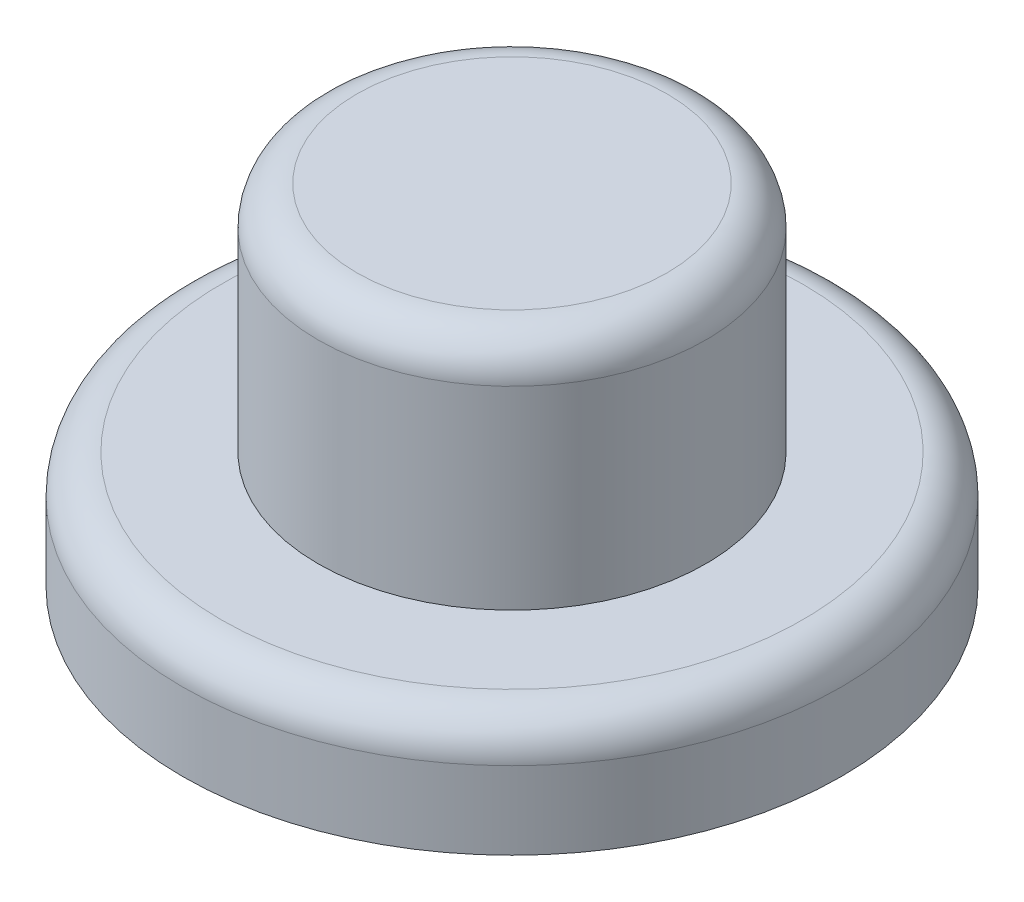
SolidWorks part; units mm, degrees
ref_plane "Front Plane" through (0, 0, 0) normal (0, 0, 1) x (1, 0, 0)
ref_plane "Top Plane" through (0, 0, 0) normal (0, 1, 0) x (1, 0, 0)
ref_plane "Right Plane" through (0, 0, 0) normal (1, 0, 0) x (0, 0, -1)
sketch "Sketch1" plane through (0, 0, 0) normal (0, 1, 0) x (1, 0, 0)
  circle A0 centre (-51.1202, 0) radius 8.5
extrude "Boss-Extrude1" add sketch "Sketch1" along normal blind 3
sketch "Sketch2" plane through (0, 3, 0) normal (0, 1, 0) x (1, 0, 0)
  circle A0 centre (-51.1202, 0) radius 5
  circle A1 centre (-51.1202, 0) radius 8.5 construction
fillet "Fillet2" radius 1 1 edges at (-51.1202, 3, 8.5)
extrude "Boss-Extrude3" add sketch "Sketch2" along normal blind 6 contours A0
fillet "Fillet4" radius 1 1 edges at (-51.1202, 9, 5)
equation "\".5.00mm\"=1"
